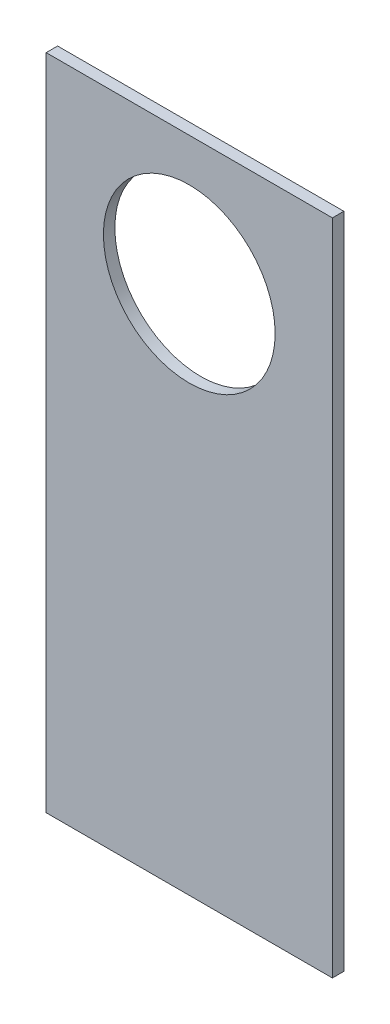
SolidWorks part; units mm, degrees
ref_plane "前视基准面" through (0, 0, 0) normal (0, 0, 1) x (1, 0, 0)
ref_plane "上视基准面" through (0, 0, 0) normal (0, 1, 0) x (1, 0, 0)
ref_plane "右视基准面" through (0, 0, 0) normal (1, 0, 0) x (0, 0, -1)
other "Configuration Table"
sketch "草图1" plane through (0, 0, 0) normal (0, 0, 1) x (1, 0, 0)
  line L0 (0, 0) -> (0, 498.031) construction
  line L1 (100, 0) -> (-100, 0)
  line L2 (-100, 0) -> (-100, 460)
  line L3 (-100, 460) -> (100, 460)
  line L4 (100, 0) -> (100, 460)
  point P7 (0, 460)
  dimension "D1" = 460
  dimension "D2" = 100
extrude "凸台-拉伸1" add sketch "草图1" along normal blind 8
sketch "草图2" plane through (0, 0, 0) normal (0, 0, -1) x (-1, 0, 0)
  line L0 (100, 0) -> (-100, 0) construction
  circle A0 centre (0, 370) radius 60
  circle A1 centre (0, 370) radius 81.25 construction
  dimension "D1" = 120
  dimension "D3" = 162.5
  dimension "D2" = 370
extrude "切除-拉伸1" cut sketch "草图2" against normal blind 10
